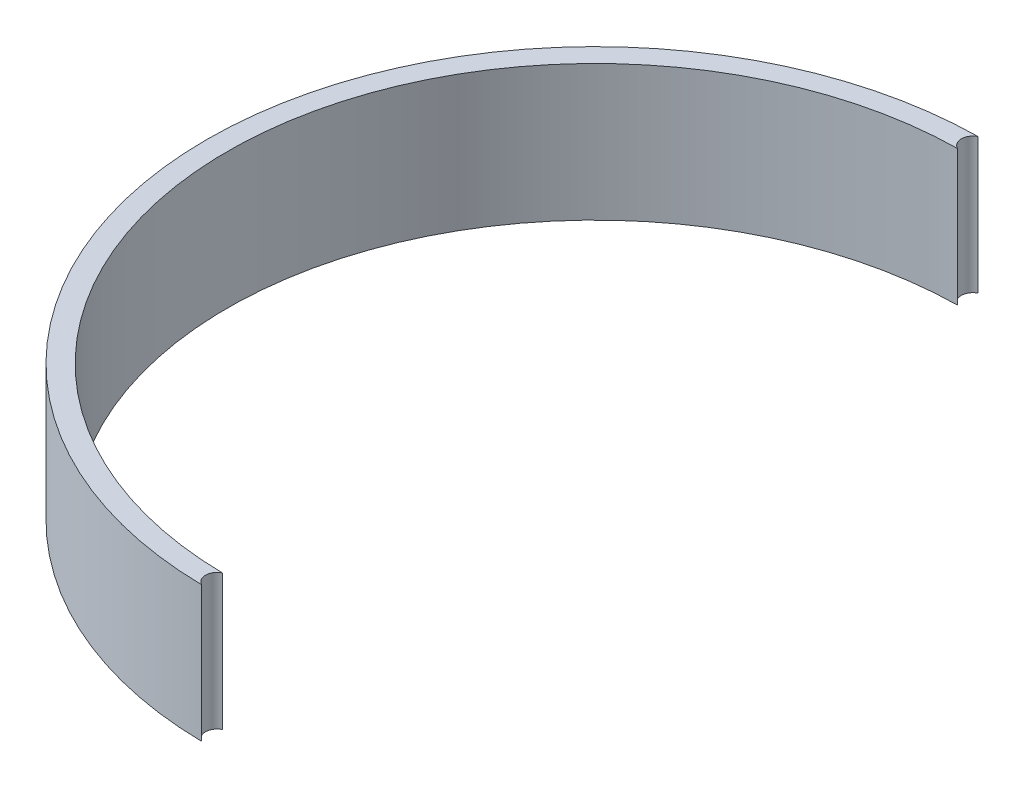
SolidWorks part; units mm, degrees
ref_plane "Front Plane" through (0, 0, 0) normal (0, 0, 1) x (1, 0, 0)
ref_plane "Top Plane" through (0, 0, 0) normal (0, 1, 0) x (1, 0, 0)
ref_plane "Right Plane" through (0, 0, 0) normal (1, 0, 0) x (0, 0, -1)
sketch "Sketch1" plane through (0, 0, 0) normal (0, 1, 0) x (1, 0, 0)
  line L0 (0, 0) -> (0, 50000) construction
  line L1 (0, -27.095) -> (0, -28.616) construction
  line L2 (0, 28.616) -> (0, 27.095)
  circle A0 centre (0, 0) radius 27.095 construction
  circle A1 centre (0, 0) radius 28.616 construction
  circle A2 centre (0, 27.8555) radius 0.85 construction
  circle A3 centre (0, -27.8555) radius 0.85 construction
  arc A4 (-0.3744, -27.0924) -> (-0.3848, -28.6134) centre (0, -27.8555) ccw
  arc A5 (-0.3848, 28.6134) -> (-0.3744, 27.0924) centre (0, 27.8555) ccw
  arc A6 (-0.3744, 27.0924) -> (-0.3744, -27.0924) centre (0, 0) ccw
  arc A7 (-0.3848, -28.6134) -> (-0.3848, 28.6134) centre (0, 0) cw
  point P12 (0, -27.095)
  point P13 (0, -28.616)
  dimension "D1" = 54.19
  dimension "D2" = 57.232
  dimension "D3" = 1.7
extrude "Boss-Extrude1" add sketch "Sketch1" along normal blind 10 contours A7 A5 A6 A4
